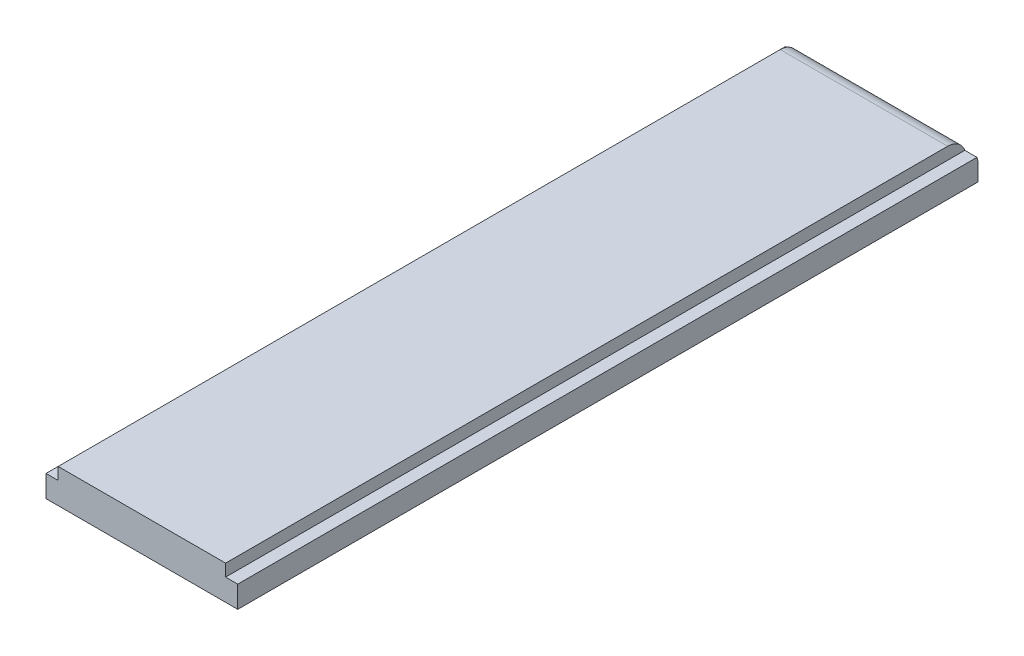
SolidWorks part; units mm, degrees
ref_plane "Plan de face" through (0, 0, 0) normal (0, 0, 1) x (1, 0, 0)
ref_plane "Plan de dessus" through (0, 0, 0) normal (0, 1, 0) x (1, 0, 0)
ref_plane "Plan de droite" through (0, 0, 0) normal (1, 0, 0) x (0, 0, -1)
sketch "Esquisse1" plane through (0, 0, 0) normal (0, 1, 0) x (1, 0, 0)
  line L1 (0, 0) -> (15.8, 0)
  line L2 (0, 0) -> (0, 62)
  line L3 (0, 62) -> (15.8, 62)
  line L4 (15.8, 0) -> (15.8, 62)
  dimension "D1" = 15.8
  dimension "D2" = 62
extrude "Boss.-Extru.1" add sketch "Esquisse1" along normal blind 1.8
sketch "Esquisse2" plane through (0, 1.8, 0) normal (0, 1, 0) x (1, 0, 0)
  line L0 (15.8, 0) -> (15.8, 62) construction
  line L1 (1, 62) -> (14.8, 62)
  line L2 (1, 62) -> (1, 1)
  line L3 (1, 1) -> (14.8, 1)
  line L4 (14.8, 62) -> (14.8, 1)
  line L5 (0, 0) -> (15.8, 0) construction
  dimension "D1" = 61
  dimension "D2" = 13.8
  dimension "D3" = 1
  dimension "D4" = 1
extrude "Boss.-Extru.2" add sketch "Esquisse2" along normal blind 1
fillet "Congé1" radius 1.5 1 edges at (7.9, 2.8, -62)
sketch "Esquisse3" plane through (0, 2.8, 0) normal (0, 1, 0) x (1, 0, 0)
  line L0 (15.8, 0) -> (15.8, 61.9142) construction
  line L1 (0, 0) -> (15.8, 0)
  line L2 (0, 0) -> (0, 1)
  line L3 (0, 1) -> (15.8, 1)
  line L4 (15.8, 0) -> (15.8, 1)
extrude "Enlèv. mat.-Extru.1" cut sketch "Esquisse3" against normal blind 10
